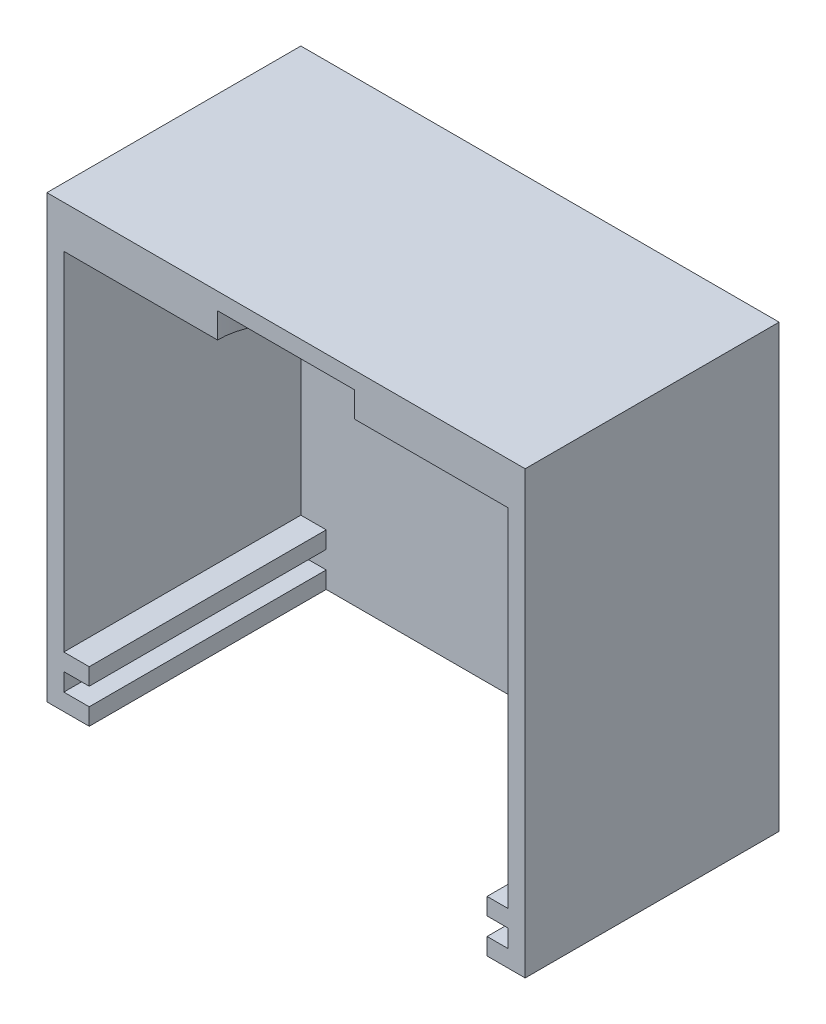
SolidWorks part; units mm, degrees
ref_plane "Front Plane" through (0, 0, 0) normal (0, 0, 1) x (1, 0, 0)
ref_plane "Top Plane" through (0, 0, 0) normal (0, 1, 0) x (1, 0, 0)
ref_plane "Right Plane" through (0, 0, 0) normal (1, 0, 0) x (0, 0, -1)
sketch "Sketch1" plane through (0, 0, 0) normal (0, 0, 1) x (1, 0, 0)
  line L1 (0, 0) -> (-56.5, 0)
  line L2 (0, 0) -> (0, 60)
  line L3 (0, 60) -> (-56.5, 60)
  line L4 (-56.5, 0) -> (-56.5, 60)
  dimension "D1" = 56.5
  dimension "D2" = 60
extrude "Boss-Extrude1" add sketch "Sketch1" along normal blind 30
shell "Shell1" thickness 2
sketch "Sketch2" plane through (0, 0, 2) normal (0, 0, 1) x (1, 0, 0)
  line L0 (-54.5, 58) -> (-54.5, 2) construction
  line L1 (-54.5, 58) -> (-2, 58)
  line L2 (-54.5, 58) -> (-54.5, 55)
  line L3 (-54.5, 55) -> (-2, 55)
  line L4 (-2, 58) -> (-2, 55)
  line L5 (-2, 2) -> (-2, 58) construction
  line L7 (-2, 58) -> (-54.5, 58) construction
  dimension "D1" = 3
  dimension "D2" = 0
extrude "Boss-Extrude2" add sketch "Sketch2" along normal blind 28
sketch "Sketch3" plane through (0, 55, 0) normal (0, -1, 0) x (1, 0, 0)
  line L0 (-54.5, 30) -> (-2, 30) construction
  line L1 (-36.35, 30) -> (-20.15, 30)
  arc A0 (-20.15, 30) -> (-36.35, 30) centre (-28.25, 30) cw
  dimension "D1" = 8.1
extrude "Cut-Extrude5" cut sketch "Sketch3" against normal blind 3
sketch "Sketch6" plane through (-54.5, 0, 0) normal (1, 0, 0) x (0, 0, -1)
  line L0 (-30, 0) -> (-30, 60) construction
  line L1 (-30, 14) -> (0, 14)
  line L2 (-30, 14) -> (-30, 12)
  line L3 (-30, 12) -> (0, 12)
  line L4 (0, 14) -> (0, 12)
  line L5 (0, 0) -> (0, 60) construction
  line L8 (-30, 60) -> (0, 60) construction
  dimension "D1" = 2
  dimension "D2" = 46
extrude "Boss-Extrude3" add sketch "Sketch6" along normal blind 3
sketch "Sketch7" plane through (-54.5, 0, 0) normal (1, 0, 0) x (0, 0, -1)
  line L0 (-30, 0) -> (-30, 60) construction
  line L1 (-30, 9.9) -> (0, 9.9)
  line L2 (-30, 9.9) -> (-30, 7.9)
  line L3 (-30, 7.9) -> (0, 7.9)
  line L4 (0, 9.9) -> (0, 7.9)
  line L5 (0, 0) -> (0, 60) construction
  line L6 (-30, 12) -> (-2, 12) construction
  dimension "D1" = 2
  dimension "D2" = 2.1
extrude "Boss-Extrude4" add sketch "Sketch7" along normal blind 3
ref_plane "Plane1" through (-28, 0, 0) normal (1, 0, 0) x (0, 0, -1)
mirror "Mirror1" about plane through (-28, 0, 0) normal (1, 0, 0) of "Boss-Extrude4", "Boss-Extrude3"
sketch "Sketch8" plane through (0, 0, 0) normal (0, -1, 0) x (1, 0, 0)
  line L1 (-56.5, 30) -> (0, 30)
  line L2 (-56.5, 30) -> (-56.5, 0)
  line L3 (-56.5, 0) -> (0, 0)
  line L4 (0, 30) -> (0, 0)
extrude "Cut-Extrude6" cut sketch "Sketch8" against normal blind 7.9
